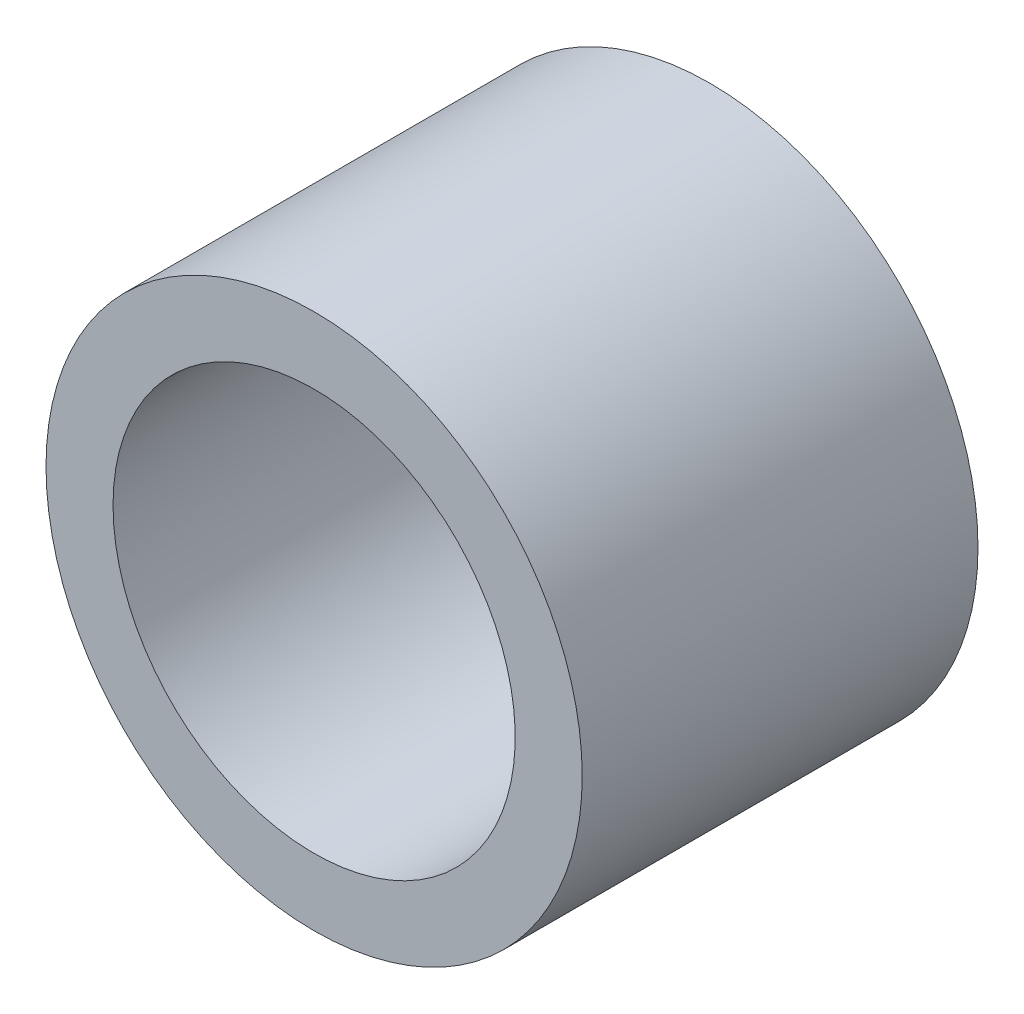
SolidWorks part; units mm, degrees
ref_plane "Front Plane" through (0, 0, 0) normal (0, 0, 1) x (1, 0, 0)
ref_plane "Top Plane" through (0, 0, 0) normal (0, 1, 0) x (1, 0, 0)
ref_plane "Right Plane" through (0, 0, 0) normal (1, 0, 0) x (0, 0, -1)
sketch "Sketch1" plane through (0, 0, 0) normal (0, 0, 1) x (1, 0, 0)
  circle A0 centre (0, 0) radius 3.15
  circle A1 centre (0, 0) radius 4.2
  dimension "D1" = 6.3
  dimension "D2" = 8.4
extrude "Boss-Extrude1" add sketch "Sketch1" along normal blind 6.2
